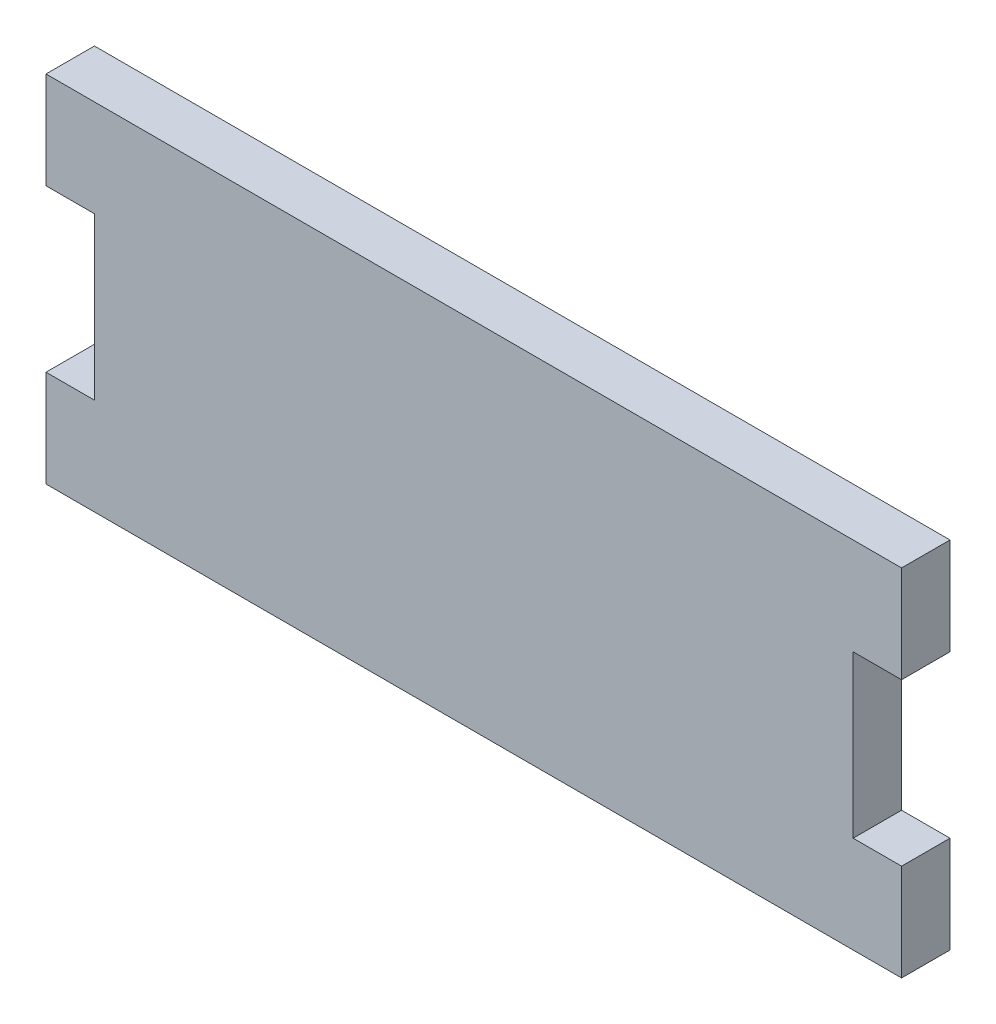
SolidWorks part; units mm, degrees
material "ABS PC"
ref_plane "Front Plane" through (0, 0, 0) normal (0, 0, 1) x (1, 0, 0)
ref_plane "Top Plane" through (0, 0, 0) normal (0, 1, 0) x (1, 0, 0)
ref_plane "Right Plane" through (0, 0, 0) normal (1, 0, 0) x (0, 0, -1)
sketch "Sketch1" plane through (0, 0, 0) normal (0, 0, 1) x (1, 0, 0)
  line L0 (-20, -11) -> (20, -11)
  line L1 (-54, 11) -> (54, 11)
  line L2 (-54, 11) -> (-54, -11)
  line L3 (-54, -11) -> (-35, -11)
  line L4 (54, 11) -> (54, -11)
  line L5 (35, -11) -> (54, -11)
  line L6 (-35, -11) -> (-35, -14)
  line L7 (-35, -14) -> (-20, -14)
  line L8 (-20, -11) -> (-20, -14)
  line L9 (0, 11) -> (0, 0) construction
  line L10 (20, -11) -> (20, -14)
  line L11 (20, -14) -> (35, -14)
  line L12 (35, -11) -> (35, -14)
  line L13 (0, 0) -> (0, -11) construction
  dimension "D1" = 22
  dimension "D2" = 108
  dimension "D3" = 15
  dimension "D4" = 3
  dimension "D5" = 40
extrude "Boss-Extrude1" add sketch "Sketch1" along normal mid plane 3 contours L1 L4 L5 L12 L11 L10 L0 L8 L7 L6 L3 L2
sketch "Sketch2" plane through (0, 0, 1.5) normal (0, 0, 1) x (1, 0, 0)
  line L0 (54, -5) -> (54, 5) construction
  line L1 (1, 5) -> (4, 5)
  line L2 (1, 5) -> (1, -5)
  line L3 (1, -5) -> (4, -5)
  line L4 (4, 5) -> (4, -5)
  line L5 (51, 5) -> (54, 5)
  line L6 (51, 5) -> (51, -5)
  line L7 (51, -5) -> (54, -5)
  line L8 (54, 5) -> (54, -5)
  line L9 (0, 0) -> (1, 0) construction
  dimension "D1" = 3
  dimension "D2" = 47
  dimension "D3" = 10
extrude "Cut-Extrude1" cut sketch "Sketch2" against normal through all
sketch "Sketch3" plane through (0, 0, 1.5) normal (0, 0, 1) x (1, 0, 0)
  line L0 (1, 5) -> (1, -5) construction
  line L1 (-54, 11) -> (1, 11)
  line L2 (-54, 11) -> (-54, -14)
  line L3 (-54, -14) -> (1, -14)
  line L4 (1, 11) -> (1, -14)
  line L5 (-35, -14) -> (-20, -14) construction
extrude "Cut-Extrude2" cut sketch "Sketch3" against normal through all
sketch "Sketch4" plane through (0, 0, -1.5) normal (0, 0, -1) x (-1, 0, 0)
  line L0 (-7, -11) -> (-7, -9)
  line L1 (-1, -11) -> (-20, -11) construction
  line L2 (-9, -7) -> (-13, -7)
  line L3 (-15, -9) -> (-15, -11)
  line L4 (-7, -11) -> (-15, -11)
  line L5 (-20, -11) -> (-20, -14) construction
  arc A0 (-15, -9) -> (-13, -7) centre (-13, -9) cw
  arc A1 (-9, -7) -> (-7, -9) centre (-9, -9) cw
  dimension "D1" = 2
  dimension "D2" = 4
  dimension "D3" = 8
  dimension "D4" = 5
extrude "Cut-Extrude3" [suppressed] cut sketch "Sketch4" against normal through all
sketch "Sketch5" plane through (0, 0, 1.5) normal (0, 0, 1) x (1, 0, 0)
  line L0 (25, 11) -> (25, 6)
  line L1 (1, 11) -> (54, 11) construction
  line L2 (25, 6) -> (23.5, 6)
  line L3 (23.5, 6) -> (23.5, 2)
  line L4 (23.5, 2) -> (25, 2)
  line L5 (25, 2) -> (25, -3)
  line L6 (25, -3) -> (30, -3)
  line L7 (30, -3) -> (30, 2)
  line L8 (30, 2) -> (31.5, 2)
  line L9 (31.5, 2) -> (31.5, 6)
  line L10 (31.5, 6) -> (30, 6)
  line L11 (30, 6) -> (30, 11)
  line L12 (30, 11) -> (25, 11)
  line L13 (27.5, -3) -> (27.5, -14) construction
  line L14 (20, -14) -> (35, -14) construction
  dimension "D1" = 5
  dimension "D2" = 8
  dimension "D3" = 5
  dimension "D4" = 5
  dimension "D5" = 4
extrude "Cut-Extrude4" [suppressed] cut sketch "Sketch5" against normal through all
sketch "Sketch6" plane through (0, 0, 1.5) normal (0, 0, 1) x (1, 0, 0)
  line L1 (20, -11) -> (35, -11)
  line L2 (20, -11) -> (20, -14)
  line L3 (20, -14) -> (35, -14)
  line L4 (35, -11) -> (35, -14)
extrude "Cut-Extrude5" cut sketch "Sketch6" against normal through all
ref_plane "Plane1" through (27.5, 0, 0) normal (1, 0, 0) x (0, 0, -1)
